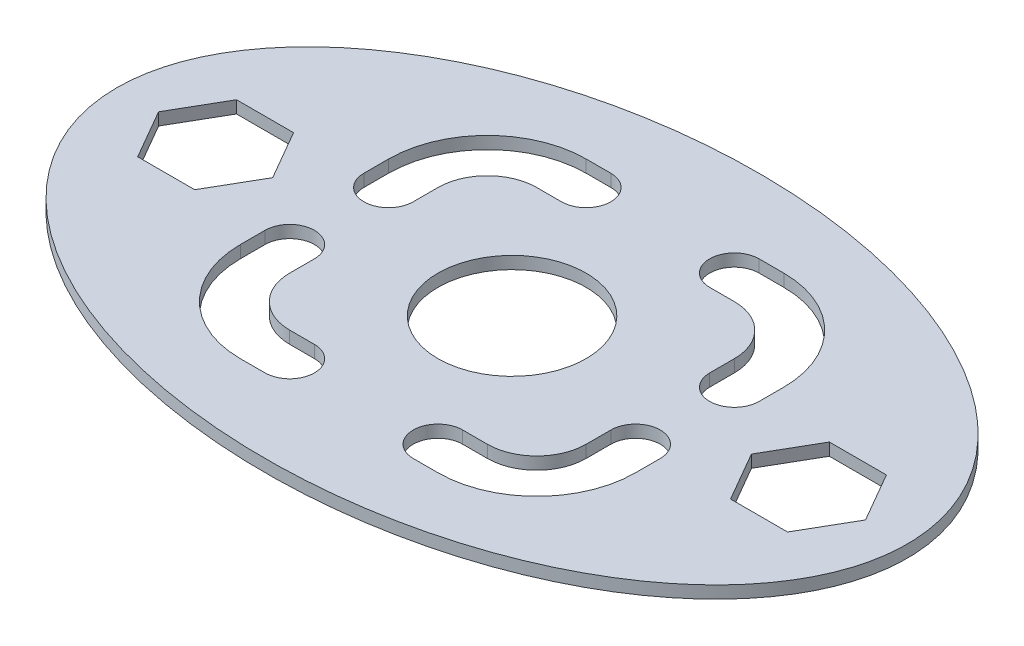
SolidWorks part; units mm, degrees
ref_plane "Front Plane" through (0, 0, 0) normal (0, 0, 1) x (1, 0, 0)
ref_plane "Top Plane" through (0, 0, 0) normal (0, 1, 0) x (1, 0, 0)
ref_plane "Right Plane" through (0, 0, 0) normal (1, 0, 0) x (0, 0, -1)
sketch "Sketch1" plane through (0, 0, 0) normal (0, 1, 0) x (1, 0, 0)
  line L1 (-61.5353, 0) -> (-68.8677, 12.7)
  line L2 (-68.8677, 12.7) -> (-83.5323, 12.7)
  line L3 (-83.5323, 12.7) -> (-90.8647, 0)
  line L4 (-90.8647, 0) -> (-83.5323, -12.7)
  line L5 (-83.5323, -12.7) -> (-68.8677, -12.7)
  line L6 (-68.8677, -12.7) -> (-61.5353, 0)
  line L7 (90.8647, 0) -> (83.5323, 12.7)
  line L8 (83.5323, 12.7) -> (68.8677, 12.7)
  line L9 (68.8677, 12.7) -> (61.5353, 0)
  line L10 (61.5353, 0) -> (68.8677, -12.7)
  line L11 (68.8677, -12.7) -> (83.5323, -12.7)
  line L12 (83.5323, -12.7) -> (90.8647, 0)
  line L15 (50.8, -19.05) -> (50.8, -12.7)
  line L16 (38.1, -19.05) -> (38.1, -12.7)
  line L17 (0, -55) -> (0, 55) construction
  line L18 (25.4, -31.75) -> (19.05, -31.75)
  line L19 (25.4, -44.45) -> (19.05, -44.45)
  line L20 (-25.4, -31.75) -> (-19.05, -31.75)
  line L21 (-25.4, -44.45) -> (-19.05, -44.45)
  line L22 (-50.8, -19.05) -> (-50.8, -12.7)
  line L23 (-38.1, -19.05) -> (-38.1, -12.7)
  line L24 (-55, 0) -> (55, 0) construction
  line L25 (25.4, 31.75) -> (19.05, 31.75)
  line L26 (25.4, 44.45) -> (19.05, 44.45)
  line L27 (50.8, 19.05) -> (50.8, 12.7)
  line L28 (38.1, 19.05) -> (38.1, 12.7)
  line L29 (-25.4, 31.75) -> (-19.05, 31.75)
  line L30 (-25.4, 44.45) -> (-19.05, 44.45)
  line L31 (-50.8, 19.05) -> (-50.8, 12.7)
  line L32 (-38.1, 19.05) -> (-38.1, 12.7)
  circle A0 centre (0, 0) radius 19.05
  circle A1 centre (-76.2, 0) radius 12.7 construction
  circle A2 centre (76.2, 0) radius 12.7 construction
  arc A3 (25.4, -31.75) -> (38.1, -19.05) centre (25.4, -19.05) ccw
  arc A4 (25.4, -44.45) -> (50.8, -19.05) centre (25.4, -19.05) ccw
  arc A5 (50.8, -12.7) -> (38.1, -12.7) centre (44.45, -12.7) ccw
  arc A6 (19.05, -31.75) -> (19.05, -44.45) centre (19.05, -38.1) ccw
  arc A7 (-25.4, -31.75) -> (-38.1, -19.05) centre (-25.4, -19.05) cw
  arc A8 (-19.05, -31.75) -> (-19.05, -44.45) centre (-19.05, -38.1) cw
  arc A9 (-25.4, -44.45) -> (-50.8, -19.05) centre (-25.4, -19.05) cw
  arc A10 (-50.8, -12.7) -> (-38.1, -12.7) centre (-44.45, -12.7) cw
  arc A11 (25.4, 31.75) -> (38.1, 19.05) centre (25.4, 19.05) cw
  arc A12 (19.05, 31.75) -> (19.05, 44.45) centre (19.05, 38.1) cw
  arc A13 (25.4, 44.45) -> (50.8, 19.05) centre (25.4, 19.05) cw
  arc A14 (50.8, 12.7) -> (38.1, 12.7) centre (44.45, 12.7) cw
  arc A15 (-19.05, 31.75) -> (-19.05, 44.45) centre (-19.05, 38.1) ccw
  arc A16 (-25.4, 44.45) -> (-50.8, 19.05) centre (-25.4, 19.05) ccw
  arc A17 (-50.8, 12.7) -> (-38.1, 12.7) centre (-44.45, 12.7) ccw
  arc A18 (-25.4, 31.75) -> (-38.1, 19.05) centre (-25.4, 19.05) ccw
  ellipse E0 centre (0, 0) end of major axis (-101.6, 0) minor radius 63.5
  dimension "D3" = 38.1
  dimension "D8" = 50.8
  dimension "D9" = 25.4
  dimension "D14" = 12.7
  dimension "D15" = 12.7
  dimension "D1" = 203.2
  dimension "D2" = 127
  dimension "D4" = 25.4
  dimension "D5" = 25.4
  dimension "D6" = 152.4
  dimension "D7" = 76.2
  dimension "D10" = 6.35
  dimension "D11" = 6.35
  dimension "D12" = 6.35
  dimension "D13" = 6.35
  dimension "D16" = 19.05
  dimension "D17" = 25.4
extrude "Boss-Extrude1" add sketch "Sketch1" along normal blind 3.175
